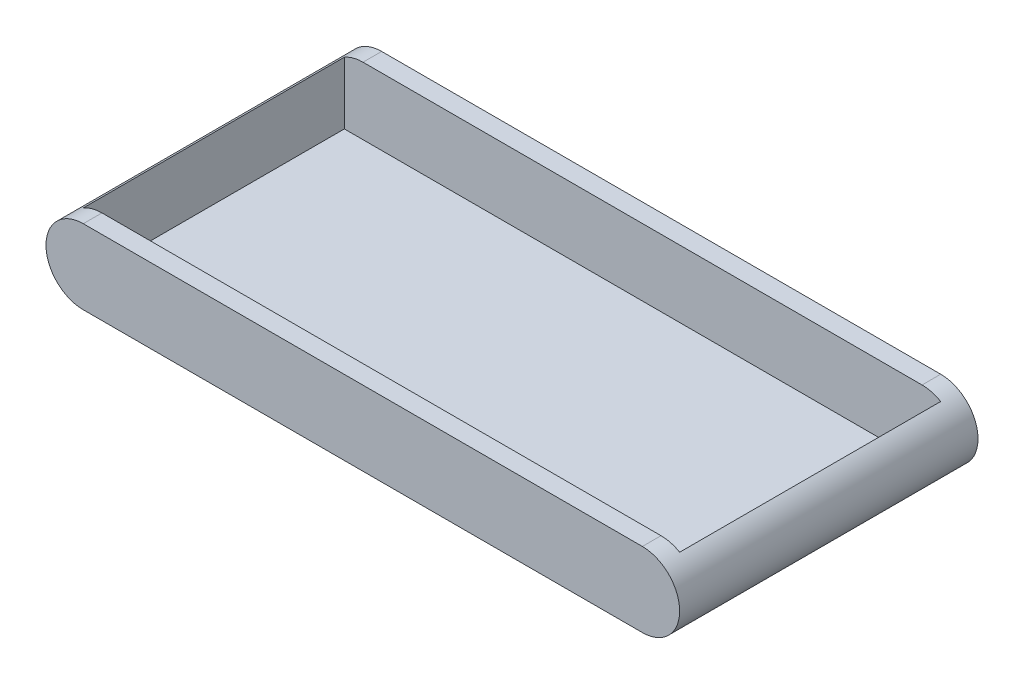
SolidWorks part; units mm, degrees
ref_plane "Front Plane" through (0, 0, 0) normal (0, 0, 1) x (1, 0, 0)
ref_plane "Top Plane" through (0, 0, 0) normal (0, 1, 0) x (1, 0, 0)
ref_plane "Right Plane" through (0, 0, 0) normal (1, 0, 0) x (0, 0, -1)
sketch "Sketch1" plane through (0, 0, 0) normal (0, 0, 1) x (1, 0, 0)
  line L0 (-3.9005, 10.8865) -> (126.0033, 10.8865)
  line L1 (-3.9005, -9.1135) -> (126.0033, -9.1135)
  line L2 (-3.9005, 10.8865) -> (-23.9005, 10.8865)
  line L4 (-23.9005, -9.1135) -> (-3.9005, -9.1135)
  arc A0 (126.0033, -9.1135) -> (126.0033, 10.8865) centre (126.0033, 0.8865) ccw
  arc A2 (-23.9005, 10.8865) -> (-23.9005, -9.1135) centre (-23.9005, 0.8865) ccw
  arc A3 (6.0752, 1.5827) -> (-13.8763, 1.5827) centre (-3.9005, 0.8865) ccw construction
  point P5 (0, 0)
  point P6 (-3.9005, 10.8865)
  dimension "D1" = 20
extrude "Boss-Extrude1" add sketch "Sketch1" against normal blind 80
sketch "Sketch2" plane through (0, 10.8865, 0) normal (0, 1, 0) x (1, 0, 0)
  line L0 (-28.9005, 75) -> (-28.9005, 5)
  line L5 (-33.9005, 80) -> (136.0033, 80) construction
  line L11 (-33.9005, 80) -> (-33.9005, 0) construction
  line L12 (-33.9005, 0) -> (136.0033, 0) construction
  line L13 (136.0033, 80) -> (136.0033, 0) construction
  line L14 (-28.9005, 5) -> (131.0033, 5)
  line L15 (131.0033, 75) -> (131.0033, 5)
  line L16 (-28.9005, 75) -> (131.0033, 75)
  dimension "D1" = 5
extrude "Cut-Extrude1" cut sketch "Sketch2" against normal blind 18
